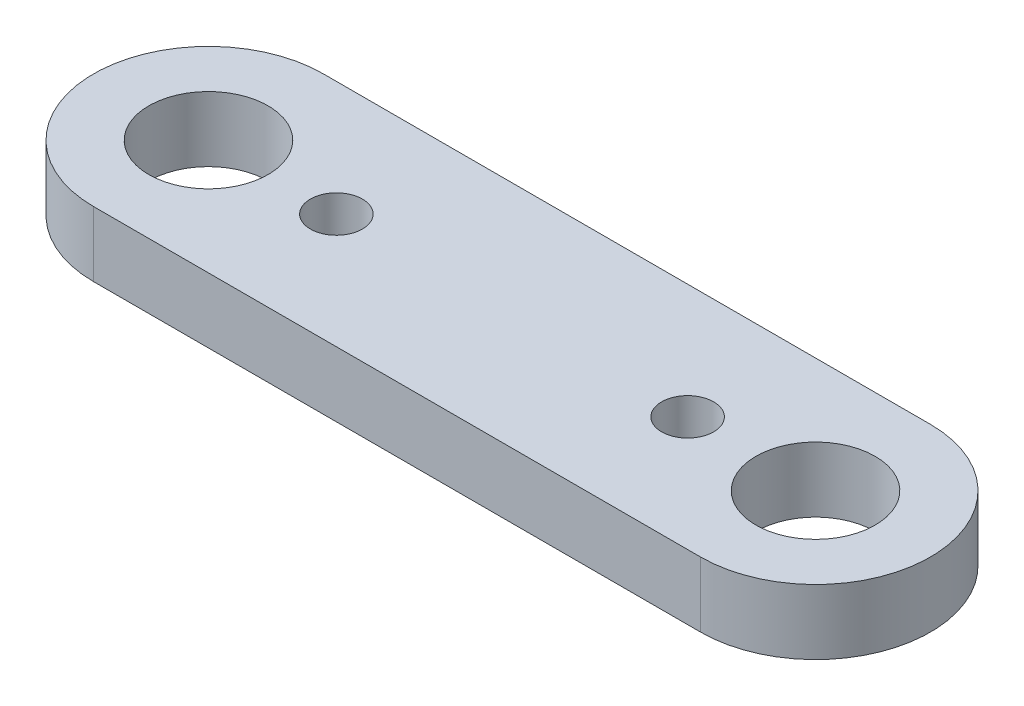
SolidWorks part; units mm, degrees
ref_plane "前视基准面" through (0, 0, 0) normal (0, 0, 1) x (1, 0, 0)
ref_plane "上视基准面" through (0, 0, 0) normal (0, 1, 0) x (1, 0, 0)
ref_plane "右视基准面" through (0, 0, 0) normal (1, 0, 0) x (0, 0, -1)
sketch "草图1" plane through (0, 0, 0) normal (0, 1, 0) x (1, 0, 0)
  line L1 (-14, 5.3) -> (14, 5.3)
  line L3 (-14, -5.3) -> (14, -5.3)
  line L5 (-14, 5.3) -> (14, -5.3) construction
  line L6 (-14, -5.3) -> (14, 5.3) construction
  line L8 (0, 0) -> (0, 6.9394) construction
  arc A0 (-14, 5.3) -> (-14, -5.3) centre (-14, 0) ccw
  circle A1 centre (-14, 0) radius 2.75
  circle A2 centre (14, 0) radius 2.75
  arc A3 (14, 5.3) -> (14, -5.3) centre (14, 0) cw
  circle A4 centre (8.1, 0) radius 1.2
  circle A5 centre (-8.1, 0) radius 1.2
  point P0 (0, 0)
  point P2 (0, 0)
  point P9 (-13.6981, 4.9583)
  point P10 (-14.6083, 0)
  point P11 (10.847, 5.3)
  point P16 (0, 0)
  point P18 (0, 0)
  point P19 (10.847, 4.9842)
  point P24 (0, 0)
  point P25 (-10, -7.2169)
  point P26 (-10, -6.5372)
  point P27 (-12.5, 0)
  point P28 (-10, -6.3472)
  point P29 (-10.8343, -4.9149)
  point P30 (-10.205, 5.2993)
  point P31 (0, 0)
  point P32 (0, 0)
  point P33 (0, 0)
  dimension "D1" = 5.5
  dimension "D2" = 28
  dimension "D8" = 2.4
  dimension "D5" = 10.6
  dimension "D9" = 16.2
extrude "凸台-拉伸1" add sketch "草图1" along normal blind 3
